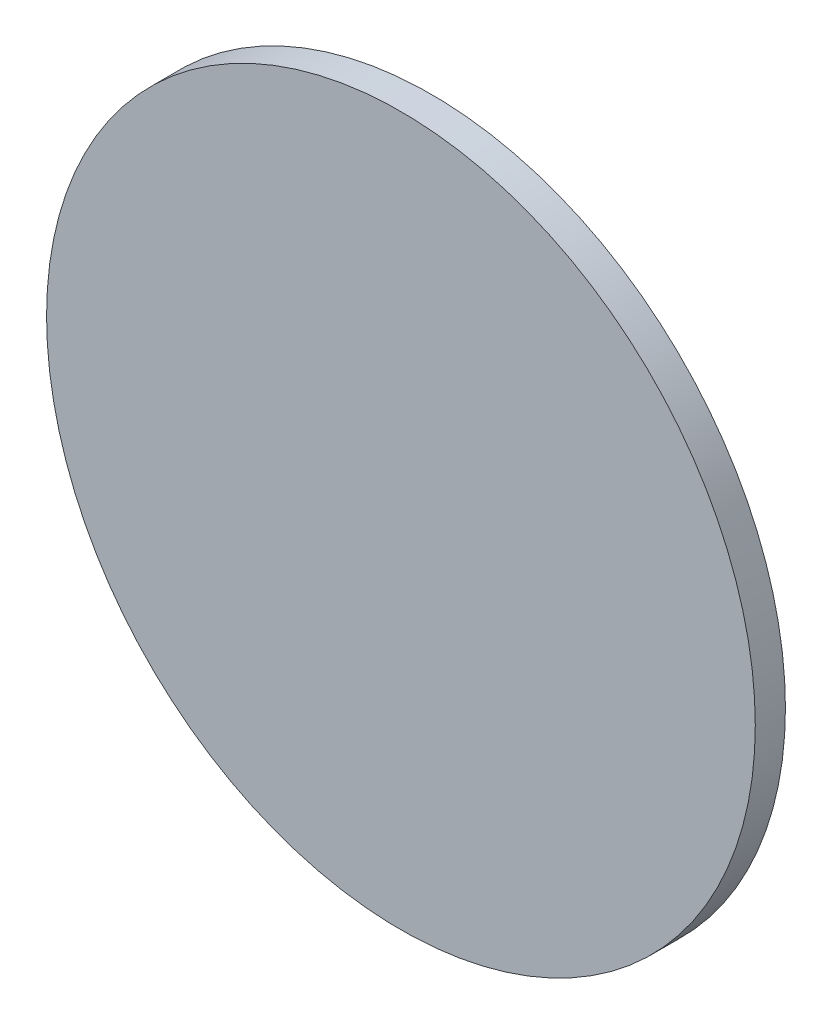
SolidWorks part; units mm, degrees
ref_plane "Front Plane" through (0, 0, 0) normal (0, 0, 1) x (1, 0, 0)
ref_plane "Top Plane" through (0, 0, 0) normal (0, 1, 0) x (1, 0, 0)
ref_plane "Right Plane" through (0, 0, 0) normal (1, 0, 0) x (0, 0, -1)
sketch "Sketch1" plane through (0, 0, 0) normal (0, 0, 1) x (1, 0, 0)
  circle A0 centre (0, 0) radius 9.525 construction
  circle A1 centre (0, 0) radius 9.525
extrude "Boss-Extrude1" add sketch "Sketch1" along normal blind 0.81
